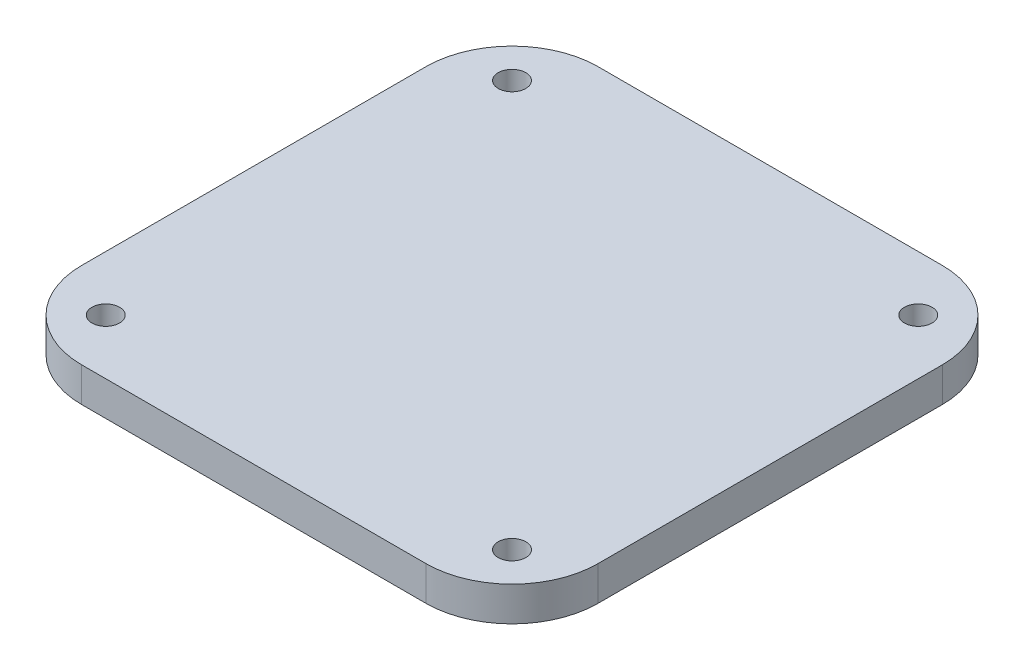
SolidWorks part; units mm, degrees
ref_plane "Front Plane" through (0, 0, 0) normal (0, 0, 1) x (1, 0, 0)
ref_plane "Top Plane" through (0, 0, 0) normal (0, 1, 0) x (1, 0, 0)
ref_plane "Right Plane" through (0, 0, 0) normal (1, 0, 0) x (0, 0, -1)
sketch "Sketch1" plane through (0, 0, 0) normal (0, 1, 0) x (1, 0, 0)
  line L0 (-19.05, 0) -> (0, 0) construction
  line L1 (19.05, -19.05) -> (-19.05, -19.05)
  line L2 (19.05, 19.05) -> (19.05, -19.05)
  line L3 (19.05, 19.05) -> (-19.05, 19.05)
  line L4 (-19.05, -19.05) -> (-19.05, 19.05)
  line L5 (19.05, -19.05) -> (-19.05, 19.05) construction
  line L6 (19.05, 19.05) -> (-19.05, -19.05) construction
  line L13 (0, 0) -> (0, -19.05) construction
  circle A0 centre (-14.986, 14.986) radius 1.016
  circle A1 centre (-14.986, -14.986) radius 1.016
  circle A2 centre (14.986, -14.986) radius 1.016
  circle A3 centre (14.986, 14.986) radius 1.016
  point P0 (0, 0)
  point P6 (0, 0)
  point P8 (0, 0)
  dimension "D1" = 2.032
  dimension "D4" = 29.972
  dimension "D5" = 29.972
  dimension "D2" = 38.1
  dimension "1.50" = 38.1
extrude "Boss-Extrude1" add sketch "Sketch1" along normal blind 2.54
fillet "Fillet1" radius 6.35 4 edges at (-19.05, 1.27, -19.05) (-19.05, 1.27, 19.05) (19.05, 1.27, -19.05) (19.05, 1.27, 19.05)
fillet "Fillet2" radius 0.5 4 edges at (14.986, 0, 16.002) (-14.986, 0, 16.002) (-14.986, 0, -13.97) (14.986, 0, -13.97)
